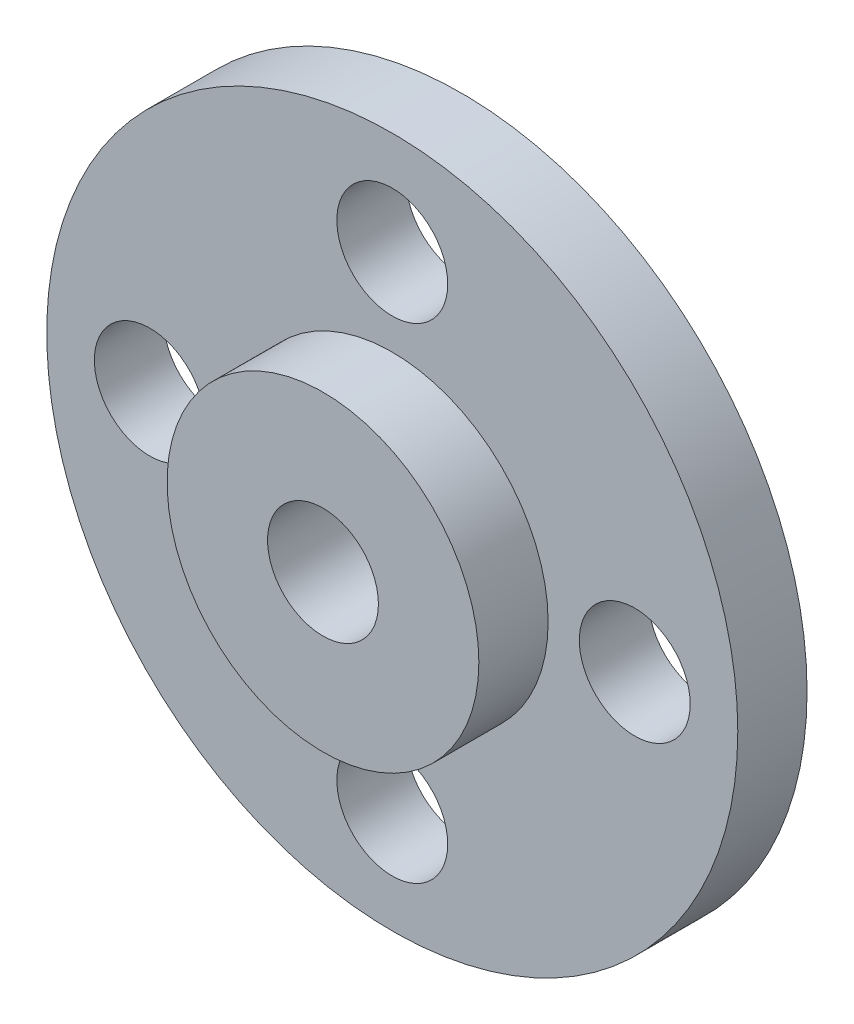
SolidWorks part; units mm, degrees
ref_plane "正面" through (0, 0, 0) normal (0, 0, 1) x (1, 0, 0)
ref_plane "平面" through (0, 0, 0) normal (0, 1, 0) x (1, 0, 0)
ref_plane "右側面" through (0, 0, 0) normal (1, 0, 0) x (0, 0, -1)
sketch "ｽｹｯﾁ1" plane through (0, 0, 0) normal (0, 0, 1) x (1, 0, 0)
  circle A0 centre (0, 0) radius 9.975
  dimension "D1" = 19.95
extrude "ﾎﾞｽ - 押し出し1" add sketch "ｽｹｯﾁ1" along normal blind 2
sketch "ｽｹｯﾁ2" plane through (0, 0, 2) normal (0, 0, 1) x (1, 0, 0)
  circle A0 centre (0, 0) radius 4.5
  dimension "D1" = 9
extrude "ﾎﾞｽ - 押し出し2" add sketch "ｽｹｯﾁ2" along normal blind 2
sketch "ｽｹｯﾁ3" plane through (0, 0, 4) normal (0, 0, 1) x (1, 0, 0)
  circle A0 centre (0, 0) radius 1.6
  dimension "D1" = 3.2
extrude "ｶｯﾄ - 押し出し1" cut sketch "ｽｹｯﾁ3" against normal through all
sketch "ｽｹｯﾁ4" plane through (0, 0, 2) normal (0, 0, 1) x (1, 0, 0)
  circle A0 centre (0, 0) radius 7 construction
  circle A1 centre (0, 7) radius 1.6
  circle A2 centre (0, -7) radius 1.6
  circle A3 centre (-7, 0) radius 1.6
  circle A4 centre (7, 0) radius 1.6
  dimension "D1" = 14
  dimension "D2" = 3.2
extrude "ｶｯﾄ - 押し出し2" cut sketch "ｽｹｯﾁ4" against normal through all
